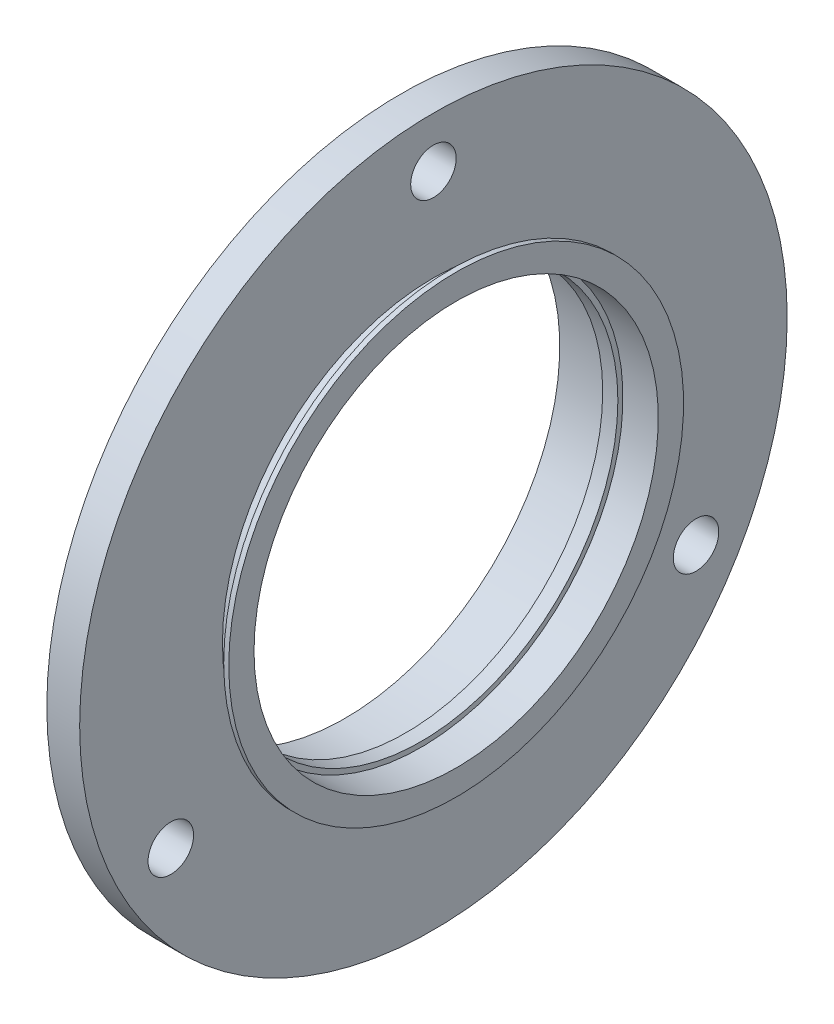
SolidWorks part; units mm, degrees
ref_plane "Piano frontale" through (0, 0, 0) normal (0, 0, 1) x (1, 0, 0)
ref_plane "Piano superiore" through (0, 0, 0) normal (0, 1, 0) x (1, 0, 0)
ref_plane "Piano destro" through (0, 0, 0) normal (1, 0, 0) x (0, 0, -1)
sketch "Schizzo1" plane through (0, 0, 0) normal (0, 0, 1) x (1, 0, 0)
  line L0 (0, 40) -> (0, 45)
  line L1 (0, 45) -> (-1, 45)
  line L2 (-4.5, 41.75) -> (-4.5, 70)
  line L3 (-4.5, 70) -> (-11, 70)
  line L4 (-11, 70) -> (-11, 47.5)
  line L5 (-11, 47.5) -> (-22, 47.5)
  line L10 (-7, 39) -> (-7, 40)
  line L11 (-7, 40) -> (0, 40)
  line L12 (-54.5549, 0) -> (51.5767, 0) construction
  line L13 (-22, 47.5) -> (-22, 42.5)
  line L14 (-22, 42.5) -> (-10, 42.5)
  line L15 (-10, 42.5) -> (-10, 39)
  line L16 (-7, 39) -> (-10, 39)
  line L18 (-4.5, 41.75) -> (-1, 41.75)
  line L19 (-1, 41.75) -> (-1, 45)
  dimension "D1" = 40
  dimension "D2" = 41.75
  dimension "D3" = 4.5
  dimension "D4" = 7
  dimension "D5" = 6.5
  dimension "D6" = 45
  dimension "10" = 11
  dimension "D7" = 70
  dimension "40" = 39
  dimension "D8" = 3
  dimension "D9" = 42.5
  dimension "D10" = 5
  dimension "D12" = 1
revolve "Rivoluzione1" add sketch "Schizzo1" angle 360 about L12
sketch "Schizzo2" plane through (-11, 0, 0) normal (-1, 0, 0) x (0, 0, 1)
  circle A0 centre (0, 60) radius 4.5
  circle A1 centre (0, 0) radius 47.5 construction
  circle A2 centre (51.9615, -30) radius 4.5
  circle A3 centre (-51.9615, -30) radius 4.5
  point P11 (0, 0)
  dimension "D1" = 9
  dimension "53" = 60
extrude "Taglio-Estrusione1" cut sketch "Schizzo2" against normal through all
